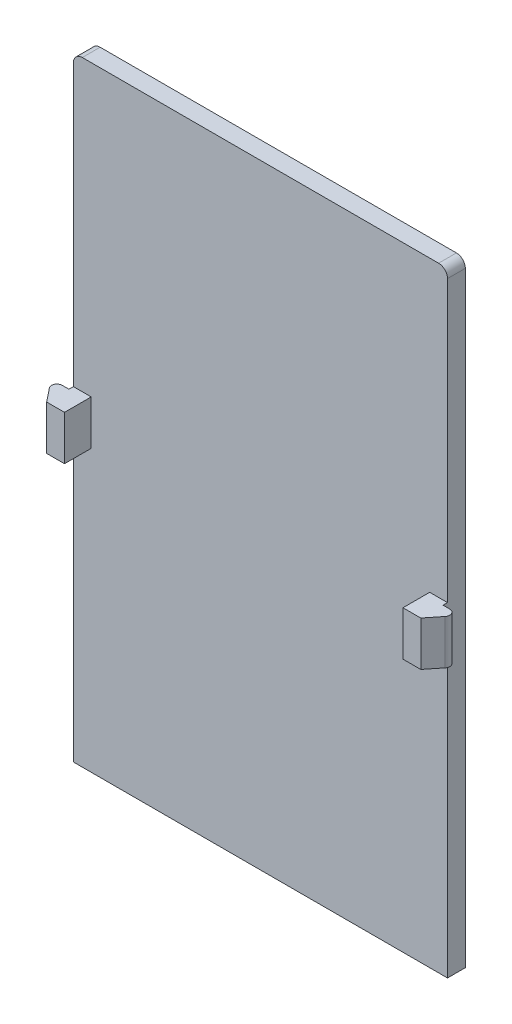
SolidWorks part; units mm, degrees
ref_plane "Front Plane" through (0, 0, 0) normal (0, 0, 1) x (1, 0, 0)
ref_plane "Top Plane" through (0, 0, 0) normal (0, 1, 0) x (1, 0, 0)
ref_plane "Right Plane" through (0, 0, 0) normal (1, 0, 0) x (0, 0, -1)
sketch "Sketch1" plane through (0, 0, 0) normal (0, 0, 1) x (1, 0, 0)
  line L1 (0, 0) -> (46, 0)
  line L2 (0, 0) -> (0, -73)
  line L3 (0, -73) -> (46, -73)
  line L4 (46, 0) -> (46, -73)
  dimension "D1" = 46
  dimension "D2" = 73
extrude "Boss-Extrude1" add sketch "Sketch1" along normal blind 2
sketch "Sketch2" plane through (0, 0, 2) normal (0, 0, 1) x (1, 0, 0)
  line L0 (0, -73) -> (46, -73) construction
  line L1 (2, -34.5) -> (4, -34.5)
  line L2 (2, -34.5) -> (2, -39.5)
  line L3 (2, -39.5) -> (4, -39.5)
  line L4 (4, -34.5) -> (4, -39.5)
  line L5 (42, -34.5) -> (44, -34.5)
  line L6 (42, -34.5) -> (42, -39.5)
  line L7 (42, -39.5) -> (44, -39.5)
  line L8 (44, -34.5) -> (44, -39.5)
  line L9 (46, -73) -> (46, 0) construction
  line L10 (0, 0) -> (0, -73) construction
  dimension "D1" = 5
  dimension "D2" = 2
  dimension "D3" = 5
  dimension "D4" = 2
  dimension "D5" = 33.5
  dimension "D6" = 33.5
  dimension "D7" = 2
  dimension "D8" = 2
extrude "Boss-Extrude2" add sketch "Sketch2" along normal blind 3
sketch "Sketch3" plane through (0, -39.5, 0) normal (0, -1, 0) x (1, 0, 0)
  line L0 (2, 5) -> (0, 5)
  line L1 (0, 5) -> (2, 7)
  line L2 (2, 7) -> (4, 7)
  line L3 (4, 7) -> (4, 5)
  line L4 (4, 5) -> (2, 5)
  line L5 (44, 5) -> (46, 5)
  line L6 (46, 5) -> (44, 7)
  line L7 (44, 7) -> (42, 7)
  line L8 (42, 7) -> (42, 5)
  line L9 (44, 5) -> (42, 5)
  dimension "D1" = 2
  dimension "D2" = 2
  dimension "D3" = 2
  dimension "D4" = 2
  dimension "D5" = 2
extrude "Boss-Extrude3" add sketch "Sketch3" against normal blind 5
fillet "Fillet1" radius 0.6 2 edges at (0, -37, 5) (46, -37, 5)
fillet "Fillet2" radius 5 2 edges at (46, 0, 1) (0, 0, 1)
sketch "Sketch5" plane through (0, 0, 2) normal (0, 0, 1) x (1, 0, 0)
  line L0 (0, -5) -> (0, -73) construction
  line L1 (46, -73) -> (0, -73)
  line L2 (46, -73) -> (46, 0)
  line L3 (46, 0) -> (0, 0)
  line L4 (0, -73) -> (0, 0)
  line L5 (41, 0) -> (5, 0) construction
  line L6 (2, -71) -> (2, -2)
  line L7 (44, -2) -> (2, -2)
  line L8 (44, -71) -> (44, -2)
  line L9 (44, -71) -> (2, -71)
  dimension "D1" = 0
  dimension "D2" = 0
  dimension "D3" = 2
extrude "Cut-Extrude1" cut sketch "Sketch5" against normal blind 10
fillet "Fillet3" radius 1 2 edges at (44, -2, 1) (2, -2, 1)
sketch "Sketch6" plane through (0, -39.5, 0) normal (0, -1, 0) x (1, 0, 0)
  line L0 (4, 7) -> (4, 2) construction
  line L1 (4, 5) -> (-0.3123, 5)
  line L2 (4, 5) -> (4, 7.938)
  line L3 (4, 7.938) -> (-0.3123, 7.938)
  line L4 (-0.3123, 5) -> (-0.3123, 7.938)
  line L5 (42, 7) -> (42, 2) construction
  line L6 (42, 5) -> (46.6868, 5)
  line L7 (42, 5) -> (42, 7.6579)
  line L8 (42, 7.6579) -> (46.6868, 7.6579)
  line L9 (46.6868, 5) -> (46.6868, 7.6579)
extrude "Cut-Extrude2" cut sketch "Sketch6" against normal blind 10
sketch "Sketch7" plane through (0, -39.5, 0) normal (0, -1, 0) x (1, 0, 0)
  line L0 (2, 2.5) -> (0, 2.5)
  line L1 (2, 5) -> (2, 2) construction
  line L2 (0, 2.5) -> (2, 5)
  line L3 (2, 5) -> (4, 5)
  line L4 (4, 5) -> (4, 2.5)
  line L5 (4, 5) -> (4, 2) construction
  line L6 (4, 2.5) -> (2, 2.5)
  line L7 (42, 2.5) -> (46, 2.5)
  line L8 (42, 5) -> (42, 2) construction
  line L9 (46, 2.5) -> (44, 5)
  line L10 (44, 5) -> (42, 5)
  line L11 (42, 5) -> (42, 2.5)
  line L12 (2, 2) -> (4, 2) construction
  line L13 (44, 5) -> (44, 2) construction
  dimension "D1" = 0.5
  dimension "D2" = 2
  dimension "D3" = 2
extrude "Boss-Extrude4" add sketch "Sketch7" against normal up to surface (5 mm away) up to face at (3, -34.5, 3.5)
fillet "Fillet4" radius 0.6 2 edges at (0, -37, 2.5) (46, -37, 2.5)
